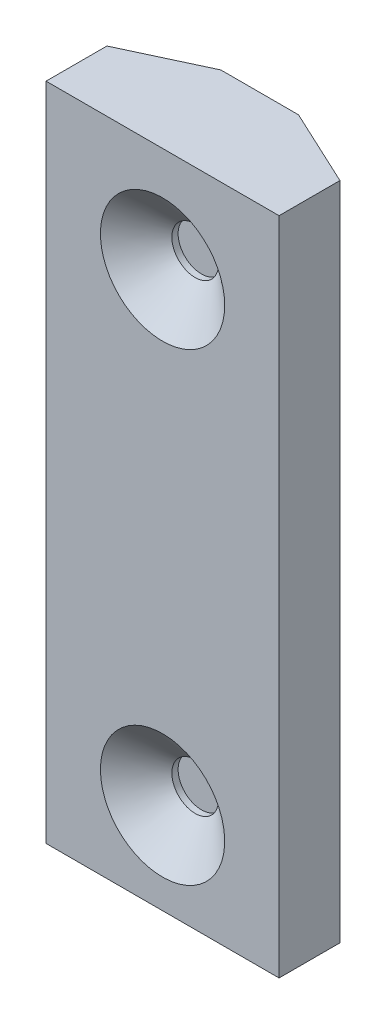
SolidWorks part; units mm, degrees
material "PLA"
ref_plane "Спереди" through (0, 0, 0) normal (0, 0, 1) x (1, 0, 0)
ref_plane "Сверху" through (0, 0, 0) normal (0, 1, 0) x (1, 0, 0)
ref_plane "Справа" through (0, 0, 0) normal (1, 0, 0) x (0, 0, -1)
sketch "Эскиз1" plane through (0, 0, 0) normal (0, 1, 0) x (1, 0, 0)
  line L0 (3, 0) -> (-3, 0)
  line L1 (-3, 0) -> (-3, 1.5674)
  line L2 (-3, 1.5674) -> (-1, 2.5)
  line L3 (-1, 2.5) -> (1, 2.5)
  line L4 (1, 2.5) -> (3, 1.5674)
  line L5 (3, 1.5674) -> (3, 0)
  line L6 (0, -4.8474) -> (0, 4.8474) construction
  point P4 (0, 0)
  point P12 (0, 0)
  dimension "D1" = 6
  dimension "D2" = 65
  dimension "D3" = 2.5
  dimension "D4" = 2
extrude "Бобышка-Вытянуть1" add sketch "Эскиз1" along normal blind 17
sketch "Эскиз2" plane through (0, 0, 0) normal (0, 0, 1) x (1, 0, 0)
  line L0 (0, 0) -> (0, 17) construction
  line L1 (-3, 17) -> (3, 17) construction
  line L2 (-3, 0) -> (3, 0) construction
  circle A0 centre (0, 2.35) radius 0.6
  circle A1 centre (0, 14.3) radius 0.6
  dimension "D3" = 1.2
  dimension "D1" = 2.35
  dimension "D2" = 11.95
extrude "Вырез-Вытянуть1" cut sketch "Эскиз2" against normal blind 1
chamfer "Фаска1" distance 1 angle 40 2 edges at (0.6, 2.35, 0) (0.6, 14.3, 0)
